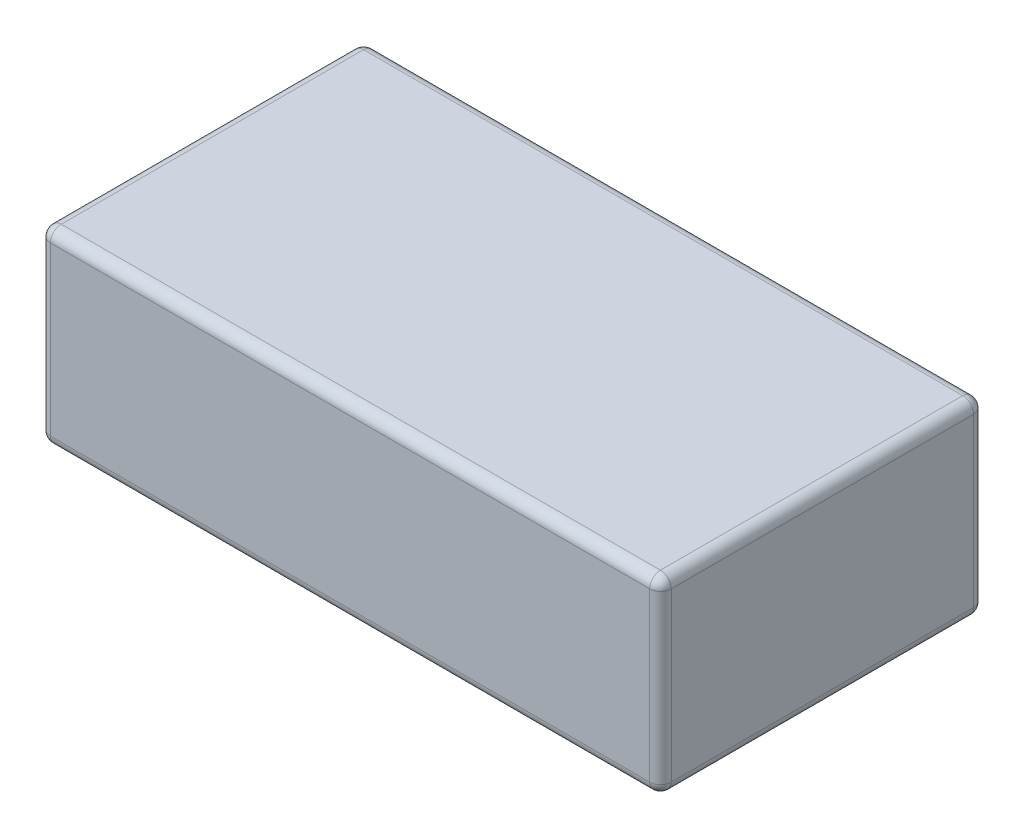
SolidWorks part; units mm, degrees
ref_plane "Front Plane" through (0, 0, 0) normal (0, 0, 1) x (1, 0, 0)
ref_plane "Top Plane" through (0, 0, 0) normal (0, 1, 0) x (1, 0, 0)
ref_plane "Right Plane" through (0, 0, 0) normal (1, 0, 0) x (0, 0, -1)
sketch "Sketch1" plane through (0, 0, 0) normal (0, 0, 1) x (1, 0, 0)
  line L1 (-57.5, -17.5) -> (57.5, -17.5)
  line L2 (-57.5, -17.5) -> (-57.5, 17.5)
  line L3 (-57.5, 17.5) -> (57.5, 17.5)
  line L4 (57.5, -17.5) -> (57.5, 17.5)
  line L5 (-57.5, -17.5) -> (57.5, 17.5) construction
  line L6 (-57.5, 17.5) -> (57.5, -17.5) construction
  point P0 (0, 0)
  dimension "D1" = 35
  dimension "D2" = 115
extrude "Boss-Extrude1" add sketch "Sketch1" along normal blind 60
fillet "Fillet1" radius 2 12 edges at (-57.5, -17.5, 30) (-57.5, 0, 60) (0, -17.5, 60) (-57.5, 17.5, 30) (-57.5, 0, 0) (0, 17.5, 0) (0, -17.5, 0) (57.5, -17.5, 30) (57.5, 0, 0) (57.5, 0, 60) (57.5, 17.5, 30) (0, 17.5, 60)
